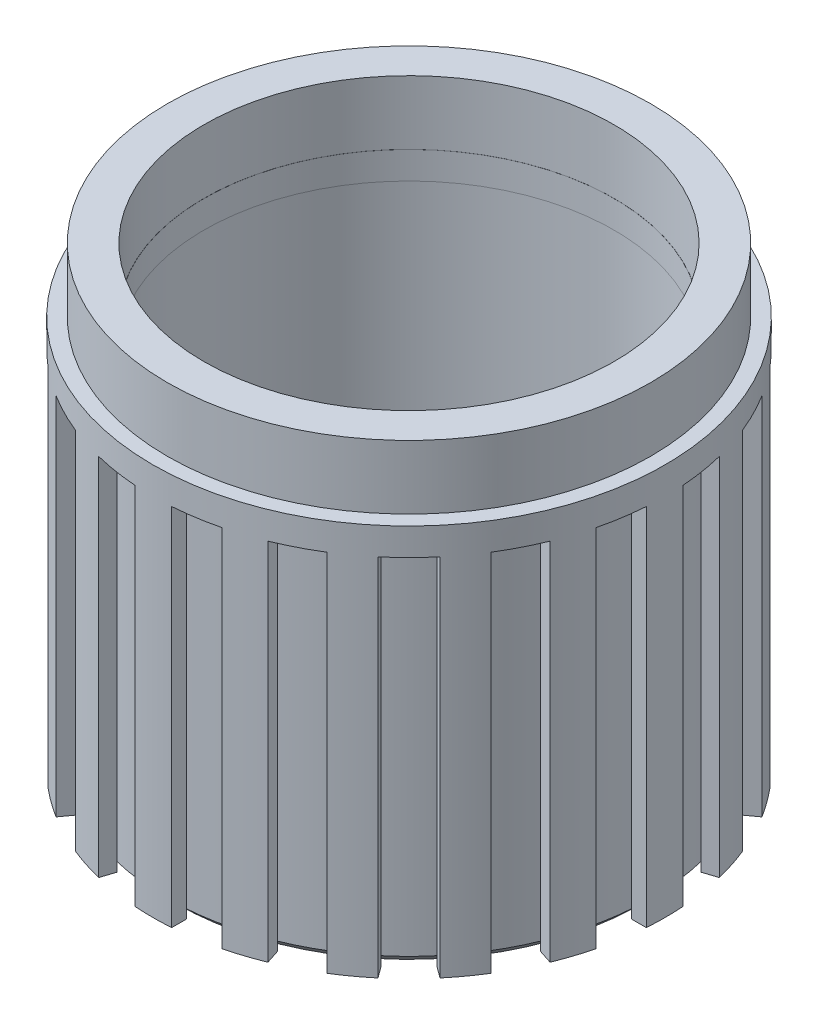
SolidWorks part; units mm, degrees
ref_plane "前视基准面" through (0, 0, 0) normal (0, 0, 1) x (1, 0, 0)
ref_plane "上视基准面" through (0, 0, 0) normal (0, 1, 0) x (1, 0, 0)
ref_plane "右视基准面" through (0, 0, 0) normal (1, 0, 0) x (0, 0, -1)
sketch "草图1" plane through (0, 0, 0) normal (0, 1, 0) x (1, 0, 0)
  circle A0 centre (0, 0) radius 13.25
  dimension "D1" = 26.5
extrude "拉伸1" add sketch "草图1" along normal blind 25
shell "抽壳1" thickness 2
chamfer "倒角1" distance 0.5 angle 45 1 edges at (0, 0, 13.25)
sketch "草图2" plane through (0, 0, 0) normal (0, -1, 0) x (1, 0, 0)
  line L0 (5.0339, 12.2565) -> (5.2817, 13.0194)
  line L1 (1, 13.2122) -> (1, 14.0144)
  line L2 (-1, 13.2122) -> (-1, 14.0144)
  line L3 (3.1317, 12.8746) -> (3.3796, 13.6375)
  line L4 (8.575, 10.1011) -> (9.0465, 10.7501)
  line L5 (6.9569, 11.2767) -> (7.4284, 11.9256)
  line L6 (11.2767, 6.9569) -> (11.9256, 7.4284)
  line L7 (10.1011, 8.575) -> (10.7501, 9.0465)
  line L8 (12.8746, 3.1317) -> (13.6375, 3.3796)
  line L9 (12.2565, 5.0339) -> (13.0194, 5.2817)
  line L10 (13.2122, -1) -> (14.0144, -1)
  line L11 (13.2122, 1) -> (14.0144, 1)
  line L12 (12.2565, -5.0339) -> (13.0194, -5.2817)
  line L13 (12.8746, -3.1317) -> (13.6375, -3.3796)
  line L14 (10.1011, -8.575) -> (10.7501, -9.0465)
  line L15 (11.2767, -6.9569) -> (11.9256, -7.4284)
  line L16 (6.9569, -11.2767) -> (7.4284, -11.9256)
  line L17 (8.575, -10.1011) -> (9.0465, -10.7501)
  line L18 (3.1317, -12.8746) -> (3.3796, -13.6375)
  line L19 (5.0339, -12.2565) -> (5.2817, -13.0194)
  line L20 (-1, -13.2122) -> (-1, -14.0144)
  line L21 (1, -13.2122) -> (1, -14.0144)
  line L22 (-5.0339, -12.2565) -> (-5.2817, -13.0194)
  line L23 (-3.1317, -12.8746) -> (-3.3796, -13.6375)
  line L24 (-8.575, -10.1011) -> (-9.0465, -10.7501)
  line L25 (-6.9569, -11.2767) -> (-7.4284, -11.9256)
  line L26 (-11.2767, -6.9569) -> (-11.9256, -7.4284)
  line L27 (-10.1011, -8.575) -> (-10.7501, -9.0465)
  line L28 (-12.8746, -3.1317) -> (-13.6375, -3.3796)
  line L29 (-12.2565, -5.0339) -> (-13.0194, -5.2817)
  line L30 (-13.2122, 1) -> (-14.0144, 1)
  line L31 (-13.2122, -1) -> (-14.0144, -1)
  line L32 (-12.2565, 5.0339) -> (-13.0194, 5.2817)
  line L33 (-12.8746, 3.1317) -> (-13.6375, 3.3796)
  line L34 (-10.1011, 8.575) -> (-10.7501, 9.0465)
  line L35 (-11.2767, 6.9569) -> (-11.9256, 7.4284)
  line L36 (-6.9569, 11.2767) -> (-7.4284, 11.9256)
  line L37 (-8.575, 10.1011) -> (-9.0465, 10.7501)
  line L38 (-3.1317, 12.8746) -> (-3.3796, 13.6375)
  line L39 (-5.0339, 12.2565) -> (-5.2817, 13.0194)
  arc A0 (1, 14.0144) -> (-1, 14.0144) centre (0, 0) ccw
  circle A1 centre (0, 0) radius 13.25 construction
  arc A2 (-1, 13.2122) -> (1, 13.2122) centre (0, 0) cw
  arc A3 (3.1317, 12.8746) -> (5.0339, 12.2565) centre (0, 0) cw
  arc A4 (5.2817, 13.0194) -> (3.3796, 13.6375) centre (0, 0) ccw
  arc A5 (6.9569, 11.2767) -> (8.575, 10.1011) centre (0, 0) cw
  arc A6 (9.0465, 10.7501) -> (7.4284, 11.9256) centre (0, 0) ccw
  arc A7 (10.1011, 8.575) -> (11.2767, 6.9569) centre (0, 0) cw
  arc A8 (11.9256, 7.4284) -> (10.7501, 9.0465) centre (0, 0) ccw
  arc A9 (12.2565, 5.0339) -> (12.8746, 3.1317) centre (0, 0) cw
  arc A10 (13.6375, 3.3796) -> (13.0194, 5.2817) centre (0, 0) ccw
  arc A11 (13.2122, 1) -> (13.2122, -1) centre (0, 0) cw
  arc A12 (14.0144, -1) -> (14.0144, 1) centre (0, 0) ccw
  arc A13 (12.8746, -3.1317) -> (12.2565, -5.0339) centre (0, 0) cw
  arc A14 (13.0194, -5.2817) -> (13.6375, -3.3796) centre (0, 0) ccw
  arc A15 (11.2767, -6.9569) -> (10.1011, -8.575) centre (0, 0) cw
  arc A16 (10.7501, -9.0465) -> (11.9256, -7.4284) centre (0, 0) ccw
  arc A17 (8.575, -10.1011) -> (6.9569, -11.2767) centre (0, 0) cw
  arc A18 (7.4284, -11.9256) -> (9.0465, -10.7501) centre (0, 0) ccw
  arc A19 (5.0339, -12.2565) -> (3.1317, -12.8746) centre (0, 0) cw
  arc A20 (3.3796, -13.6375) -> (5.2817, -13.0194) centre (0, 0) ccw
  arc A21 (1, -13.2122) -> (-1, -13.2122) centre (0, 0) cw
  arc A22 (-1, -14.0144) -> (1, -14.0144) centre (0, 0) ccw
  arc A23 (-3.1317, -12.8746) -> (-5.0339, -12.2565) centre (0, 0) cw
  arc A24 (-5.2817, -13.0194) -> (-3.3796, -13.6375) centre (0, 0) ccw
  arc A25 (-6.9569, -11.2767) -> (-8.575, -10.1011) centre (0, 0) cw
  arc A26 (-9.0465, -10.7501) -> (-7.4284, -11.9256) centre (0, 0) ccw
  arc A27 (-10.1011, -8.575) -> (-11.2767, -6.9569) centre (0, 0) cw
  arc A28 (-11.9256, -7.4284) -> (-10.7501, -9.0465) centre (0, 0) ccw
  arc A29 (-12.2565, -5.0339) -> (-12.8746, -3.1317) centre (0, 0) cw
  arc A30 (-13.6375, -3.3796) -> (-13.0194, -5.2817) centre (0, 0) ccw
  arc A31 (-13.2122, -1) -> (-13.2122, 1) centre (0, 0) cw
  arc A32 (-14.0144, 1) -> (-14.0144, -1) centre (0, 0) ccw
  arc A33 (-12.8746, 3.1317) -> (-12.2565, 5.0339) centre (0, 0) cw
  arc A34 (-13.0194, 5.2817) -> (-13.6375, 3.3796) centre (0, 0) ccw
  arc A35 (-11.2767, 6.9569) -> (-10.1011, 8.575) centre (0, 0) cw
  arc A36 (-10.7501, 9.0465) -> (-11.9256, 7.4284) centre (0, 0) ccw
  arc A37 (-8.575, 10.1011) -> (-6.9569, 11.2767) centre (0, 0) cw
  arc A38 (-7.4284, 11.9256) -> (-9.0465, 10.7501) centre (0, 0) ccw
  arc A39 (-5.0339, 12.2565) -> (-3.1317, 12.8746) centre (0, 0) cw
  arc A40 (-3.3796, 13.6375) -> (-5.2817, 13.0194) centre (0, 0) ccw
  point P5 (1, 0)
  point P7 (1, 18.9317)
  point P8 (-1, 0)
  point P9 (-1, 18.9317)
  dimension "D1" = 0.8
extrude "拉伸2" add sketch "草图2" against normal blind 20
sketch "草图3" plane through (0, 20, 0) normal (0, 1, 0) x (1, 0, 0)
  circle A0 centre (0, 0) radius 14.05
  circle A1 centre (0, 0) radius 11.245
extrude "拉伸3" add sketch "草图3" along normal blind 1.5
